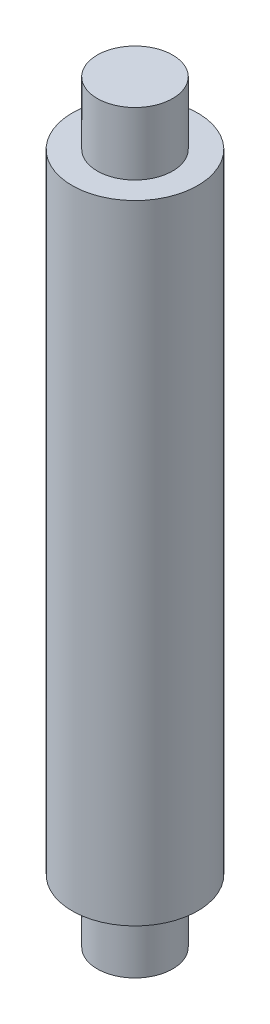
SolidWorks part; units mm, degrees
ref_plane "Alzado" through (0, 0, 0) normal (0, 0, 1) x (1, 0, 0)
ref_plane "Planta" through (0, 0, 0) normal (0, 1, 0) x (1, 0, 0)
ref_plane "Vista lateral" through (0, 0, 0) normal (1, 0, 0) x (0, 0, -1)
sketch "Croquis1" plane through (0, 0, 0) normal (0, 0, 1) x (1, 0, 0)
  line L0 (0, 0) -> (-6, 0)
  line L1 (-6, 0) -> (-6, 10)
  line L2 (-6, 10) -> (-10, 10)
  line L3 (-10, 10) -> (-10, 110)
  line L4 (-10, 110) -> (-6, 110)
  line L5 (-6, 110) -> (-6, 120)
  line L6 (-6, 120) -> (0, 120)
  line L7 (0, 120) -> (0, 0)
  dimension "D1" = 6
  dimension "D2" = 10
  dimension "D3" = 10
  dimension "D4" = 100
  dimension "D5" = 120
revolve "Revolución1" add sketch "Croquis1" angle 360 about L7
